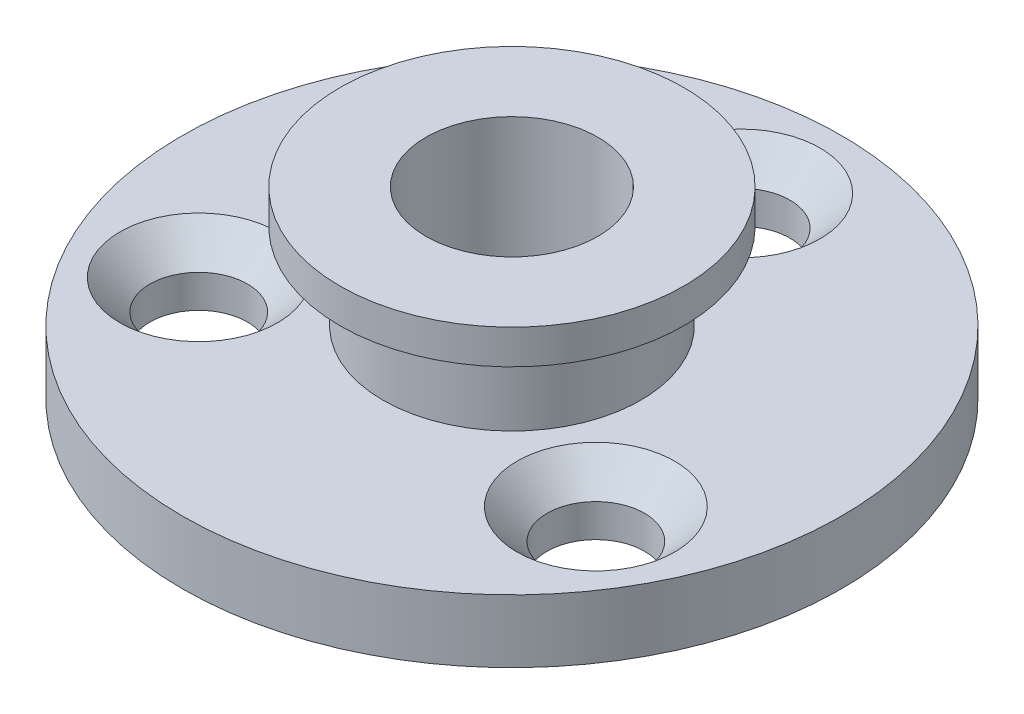
SolidWorks part; units mm, degrees
ref_plane "Plan de face" through (0, 0, 0) normal (0, 0, 1) x (1, 0, 0)
ref_plane "Plan de dessus" through (0, 0, 0) normal (0, 1, 0) x (1, 0, 0)
ref_plane "Plan de droite" through (0, 0, 0) normal (1, 0, 0) x (0, 0, -1)
sketch "Esquisse1" plane through (0, 0, 0) normal (0, 0, 1) x (1, 0, 0)
  line L0 (0, 4.6899) -> (0, -3.9873) construction
  line L1 (3, -3.2) -> (3, 3.2)
  line L2 (3, 3.2) -> (6, 3.2)
  line L3 (6, 3.2) -> (6, 2)
  line L4 (6, 2) -> (4.5, 2)
  line L5 (4.5, 2) -> (4.5, -1)
  line L6 (4.5, -1) -> (11.5, -1)
  line L7 (11.5, -1) -> (11.5, -3.2)
  line L8 (11.5, -3.2) -> (3, -3.2)
  point P5 (4.5, 0.5)
  point P12 (3, 0)
  dimension "D1" = 1.2
  dimension "D2" = 2.2
  dimension "D3" = 3
  dimension "D4" = 3
  dimension "D5" = 1.5
  dimension "D6" = 1.5
  dimension "D7" = 11.5
revolve "Révolution1" add sketch "Esquisse1" angle 360 about L0
sketch "Esquisse2" plane through (0, -1, 0) normal (0, 1, 0) x (1, 0, 0)
  line L0 (0, 0) -> (0, 8) construction
  line L1 (0, 0) -> (6.9282, -4) construction
  line L2 (0, 0) -> (-6.9282, -4) construction
  circle A0 centre (0, 0) radius 8 construction
  circle A1 centre (0, 8) radius 1.7 construction
  circle A2 centre (0, 8) radius 2.85 construction
  circle A3 centre (6.9282, -4) radius 2.85 construction
  circle A4 centre (6.9282, -4) radius 1.7 construction
  circle A5 centre (-6.9282, -4) radius 2.85 construction
  circle A6 centre (-6.9282, -4) radius 1.7 construction
  point P14 (0, 0)
  dimension "D1" = 16
  dimension "D2" = 3.4
  dimension "D3" = 5.7
  dimension "D4" = 3
sketch "Esquisse5" plane through (0, -1, 0) normal (0, 1, 0) x (1, 0, 0)
  point P0 (-6.9282, -4)
  point P3 (6.9282, -4)
  point P6 (0, 8)
hole_wizard "CSK for M3 Flat Head Machine Screw1" positions "Esquisse5" profile "Esquisse4" countersink size "M3" standard "ANSI Metric" end condition through all
sketch "Esquisse4" plane through (-6.9282, -1, 4) normal (1, 0, 0) x (0, 0, 1)
  line L0 (0, 0) -> (0, 2.2)
  line L1 (0, 2.2) -> (1.7, 2.2)
  line L2 (1.7, 2.2) -> (1.7, 1.05)
  line L3 (1.7, 1.05) -> (2.75, 0)
  line L5 (2.75, 0) -> (0, 0)
  line L6 (-1.7, 1.05) -> (-2.75, 0) construction
  line L11 (0, -6.35) -> (0, 107.95) construction
  dimension "Thru Hole Dia." = 3.4
  dimension "Thru Hole Depth" = 2.2
  dimension "Near C'Sink Dia." = 5.5
  dimension "Near C'Sink Angle" = 90
